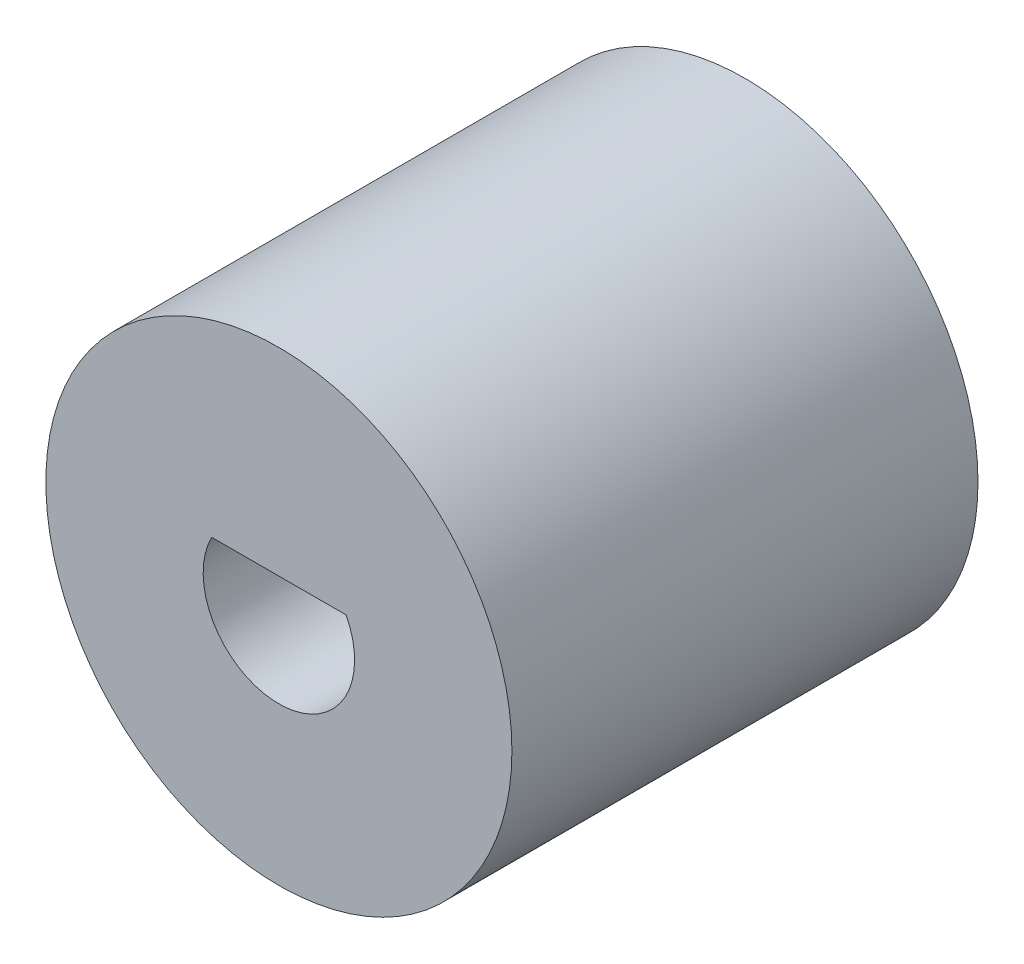
SolidWorks part; units mm, degrees
ref_plane "Front Plane" through (0, 0, 0) normal (0, 0, 1) x (1, 0, 0)
ref_plane "Top Plane" through (0, 0, 0) normal (0, 1, 0) x (1, 0, 0)
ref_plane "Right Plane" through (0, 0, 0) normal (1, 0, 0) x (0, 0, -1)
sketch "Sketch1" plane through (0, 0, 0) normal (0, 0, 1) x (1, 0, 0)
  circle A0 centre (0, 0) radius 5
  dimension "D1" = 10
extrude "Boss-Extrude1" add sketch "Sketch1" along normal blind 10
sketch "Sketch2" plane through (0, 0, 10) normal (0, 0, 1) x (1, 0, 0)
  line L0 (-1.4416, 0.75) -> (1.4416, 0.75)
  arc A0 (-1.4416, 0.75) -> (1.4416, 0.75) centre (0, 0) ccw
  dimension "D1" = 1.625
  dimension "D2" = 0.75
extrude "Cut-Extrude1" cut sketch "Sketch2" against normal blind 5
sketch "Sketch3" plane through (0, 0, 0) normal (0, 0, -1) x (-1, 0, 0)
  circle A0 centre (0, 0) radius 2.9
  dimension "D1" = 5.8
extrude "Cut-Extrude2" cut sketch "Sketch3" against normal blind 5
